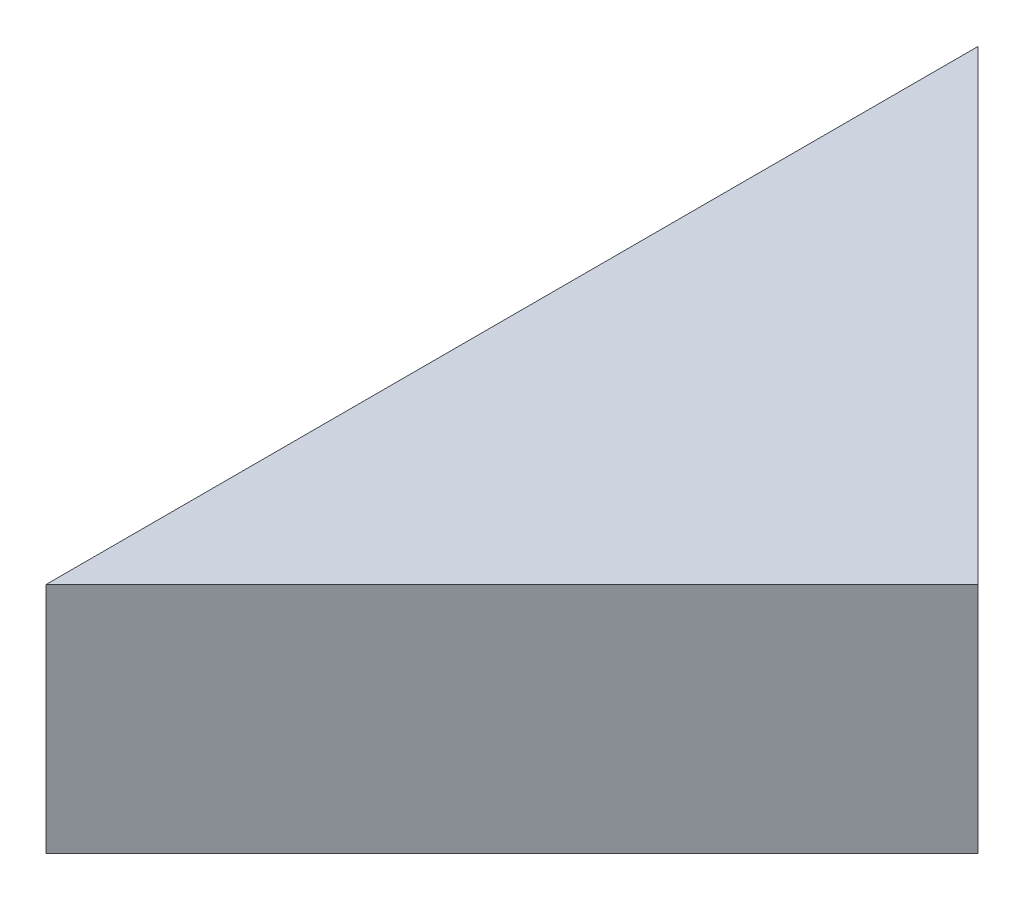
SolidWorks part; units mm, degrees
ref_plane "Front Plane" through (0, 0, 0) normal (0, 0, 1) x (1, 0, 0)
ref_plane "Top Plane" through (0, 0, 0) normal (0, 1, 0) x (1, 0, 0)
ref_plane "Right Plane" through (0, 0, 0) normal (1, 0, 0) x (0, 0, -1)
sketch "Sketch1" plane through (0, 0, 0) normal (0, 1, 0) x (1, 0, 0)
  line L0 (0, 0) -> (0, 60)
  line L1 (0, 60) -> (30, 30)
  line L2 (30, 30) -> (0, 0)
  dimension "D1" = 60
  dimension "D2" = 90
extrude "Boss-Extrude1" add sketch "Sketch1" along normal blind 15
